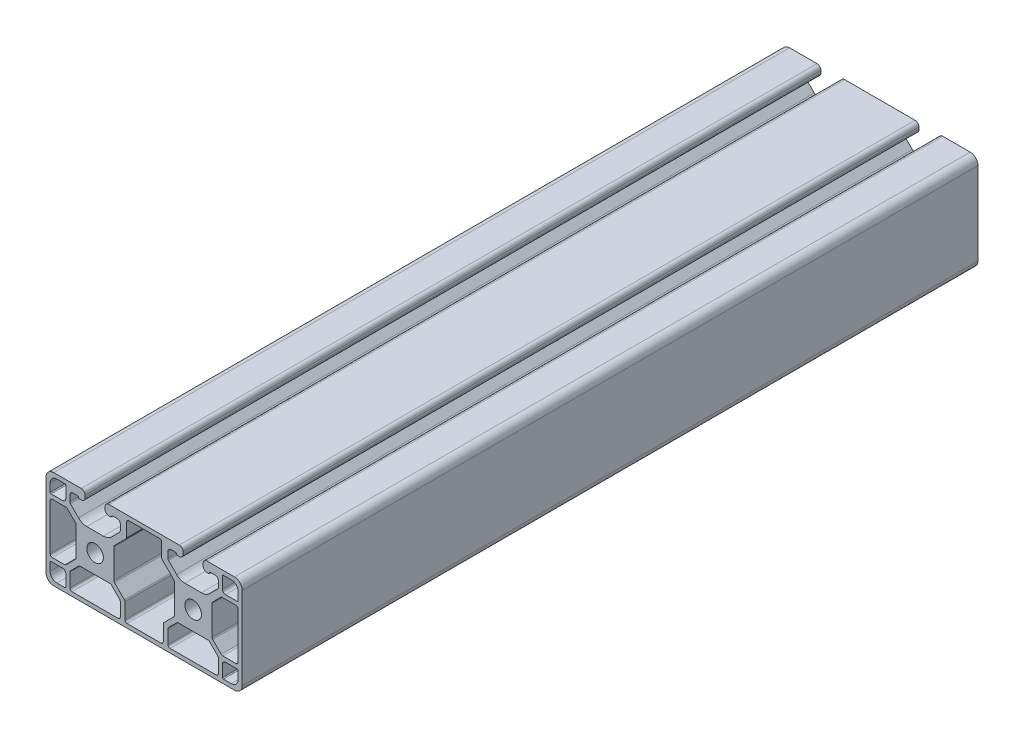
SolidWorks part; units mm, degrees
material "6105-T5 Aluminum"
ref_plane "Front Plane" through (0, 0, 0) normal (0, 0, 1) x (1, 0, 0)
ref_plane "Top Plane" through (0, 0, 0) normal (0, 1, 0) x (1, 0, 0)
ref_plane "Right Plane" through (0, 0, 0) normal (1, 0, 0) x (0, 0, -1)
sketch "Sketch1" plane through (0, 0, 0) normal (0, 0, 1) x (1, 0, 0)
  line L0 (18.3492, 15.5556) -> (18.3145, 12.3124)
  line L1 (17.9346, 11.9365) -> (13.2063, 11.9365)
  line L2 (11.9365, 13.2063) -> (11.9365, 17.9346)
  line L3 (12.3124, 18.3145) -> (15.5556, 18.3492)
  line L4 (15.5556, -18.3492) -> (12.3165, -18.3492)
  line L5 (11.9365, -17.9693) -> (11.9365, -13.2063)
  line L6 (13.2063, -11.9365) -> (17.9346, -11.9365)
  line L7 (18.3145, -12.3124) -> (18.3492, -15.5556)
  line L8 (-12.565, 11.308) -> (-7.9429, 6.6858)
  line L9 (-7.6825, 6.0573) -> (-7.6825, -5.8777)
  line L10 (-7.9429, -6.5062) -> (-11.9301, -10.4935)
  line L11 (-12.1905, -11.122) -> (-12.1905, -17.4603)
  line L12 (-13.0794, -18.3492) -> (-26.9206, -18.3492)
  line L13 (-27.8095, -17.4603) -> (-27.8095, -11.122)
  line L14 (-28.0699, -10.4935) -> (-32.0571, -6.5062)
  line L15 (-32.3175, -5.8777) -> (-32.3175, 6.0573)
  line L16 (-32.0571, 6.6858) -> (-27.435, 11.308)
  line L17 (-27.1746, 11.9365) -> (-27.1746, 17.4216)
  line L18 (-26.2857, 18.3105) -> (-13.7143, 18.3105)
  line L19 (-12.8254, 17.4216) -> (-12.8254, 11.9365)
  line L20 (-51.2824, 10.0254) -> (-47.9429, 6.6858)
  line L21 (-47.6825, 6.0573) -> (-47.6825, -5.5185)
  line L22 (-47.9429, -6.1471) -> (-51.8212, -10.0254)
  line L23 (-52.4497, -10.2857) -> (-57.4216, -10.2857)
  line L24 (-58.3105, -9.3968) -> (-58.3105, 9.3968)
  line L25 (-57.4216, 10.2857) -> (-51.911, 10.2857)
  line L26 (-58.3145, 12.3124) -> (-58.3492, 15.5556)
  line L27 (-55.5556, 18.3492) -> (-52.3124, 18.3145)
  line L28 (-51.9365, 17.9346) -> (-51.9365, 13.2063)
  line L29 (-53.2063, 11.9365) -> (-57.9346, 11.9365)
  line L30 (-52.3165, -18.3492) -> (-55.5556, -18.3492)
  line L31 (-58.3492, -15.5556) -> (-58.3145, -12.3124)
  line L32 (-57.9346, -11.9365) -> (-53.2063, -11.9365)
  line L33 (-51.9365, -13.2063) -> (-51.9365, -17.9693)
  line L34 (-46.0573, -7.6825) -> (-33.9427, -7.6825)
  line L35 (-33.3142, -7.9429) -> (-29.9746, -11.2824)
  line L36 (-29.7143, -11.911) -> (-29.7143, -17.4603)
  line L37 (-30.6032, -18.3492) -> (-49.3968, -18.3492)
  line L38 (-50.2857, -17.4603) -> (-50.2857, -11.911)
  line L39 (-50.0254, -11.2824) -> (-46.6858, -7.9429)
  line L40 (10.2857, -11.911) -> (10.2857, -17.4603)
  line L41 (9.3968, -18.3492) -> (-9.3968, -18.3492)
  line L42 (-10.2857, -17.4603) -> (-10.2857, -11.911)
  line L43 (-10.0254, -11.2824) -> (-6.6858, -7.9429)
  line L44 (-6.0573, -7.6825) -> (6.0572, -7.6825)
  line L45 (6.6858, -7.9429) -> (10.0253, -11.2824)
  line L46 (11.462, -10.0253) -> (7.9429, -6.5063)
  line L47 (7.6825, -5.8776) -> (7.6825, 6.0573)
  line L48 (7.9429, 6.6858) -> (11.2824, 10.0254)
  line L49 (11.911, 10.2857) -> (17.4216, 10.2857)
  line L50 (18.3105, 9.3968) -> (18.3105, -9.3968)
  line L51 (17.4216, -10.2857) -> (12.0906, -10.2857)
  line L52 (20, -16.8254) -> (20, 16.8254)
  line L53 (16.8254, 20) -> (5.6381, 20)
  line L54 (4.0635, 18.4254) -> (4.0635, 17.5111)
  line L55 (5.6381, 15.9365) -> (6.3446, 15.9365)
  line L56 (6.7243, 16.3032) -> (6.7253, 16.3317)
  line L57 (7.105, 16.6984) -> (9.0159, 16.6984)
  line L58 (10.2857, 15.4286) -> (10.2857, 12.9885)
  line L59 (10.0254, 12.3599) -> (6.739, 9.0736)
  line L60 (3.3808, 7.6825) -> (-3.3808, 7.6825)
  line L61 (-6.739, 9.0736) -> (-10.0254, 12.3599)
  line L62 (-10.2857, 12.9885) -> (-10.2857, 15.4286)
  line L63 (-9.0159, 16.6984) -> (-7.105, 16.6984)
  line L64 (-6.7253, 16.3317) -> (-6.7243, 16.3032)
  line L65 (-6.3446, 15.9365) -> (-5.6381, 15.9365)
  line L66 (-4.0635, 17.5111) -> (-4.0635, 18.4254)
  line L67 (-5.6381, 20) -> (-34.3619, 20)
  line L68 (-35.9365, 18.4254) -> (-35.9365, 17.5111)
  line L69 (-34.3619, 15.9365) -> (-33.6554, 15.9365)
  line L70 (-33.2757, 16.3032) -> (-33.2747, 16.3317)
  line L71 (-32.895, 16.6984) -> (-30.9841, 16.6984)
  line L72 (-29.7143, 15.4286) -> (-29.7143, 12.9885)
  line L73 (-29.9746, 12.3599) -> (-33.261, 9.0736)
  line L74 (-36.6192, 7.6825) -> (-43.3808, 7.6825)
  line L75 (-46.739, 9.0736) -> (-50.0254, 12.3599)
  line L76 (-50.2857, 12.9885) -> (-50.2857, 15.4286)
  line L77 (-49.0159, 16.6984) -> (-47.105, 16.6984)
  line L78 (-46.7253, 16.3317) -> (-46.7243, 16.3032)
  line L79 (-46.3446, 15.9365) -> (-45.6381, 15.9365)
  line L80 (-44.0635, 17.5111) -> (-44.0635, 18.4254)
  line L81 (-45.6381, 20) -> (-56.8254, 20)
  line L82 (-60, 16.8254) -> (-60, -16.8254)
  line L83 (-56.8254, -20) -> (16.8254, -20)
  arc A0 (17.9346, 11.9365) -> (18.3145, 12.3124) centre (17.9346, 12.3165) ccw
  arc A1 (11.9365, 13.2063) -> (13.2063, 11.9365) centre (13.2063, 13.2063) ccw
  arc A2 (12.3124, 18.3145) -> (11.9365, 17.9346) centre (12.3165, 17.9346) ccw
  arc A3 (18.3492, 15.5556) -> (15.5556, 18.3492) centre (15.5556, 15.5556) ccw
  arc A4 (11.9365, -17.9693) -> (12.3165, -18.3492) centre (12.3165, -17.9693) ccw
  arc A5 (13.2063, -11.9365) -> (11.9365, -13.2063) centre (13.2063, -13.2063) ccw
  arc A6 (18.3145, -12.3124) -> (17.9346, -11.9365) centre (17.9346, -12.3165) ccw
  arc A7 (15.5556, -18.3492) -> (18.3492, -15.5556) centre (15.5556, -15.5556) ccw
  arc A8 (-12.8254, 11.9365) -> (-12.565, 11.308) centre (-11.9365, 11.9365) ccw
  arc A9 (-7.6825, 6.0573) -> (-7.9429, 6.6858) centre (-8.5714, 6.0573) ccw
  arc A10 (-7.9429, -6.5062) -> (-7.6825, -5.8777) centre (-8.5714, -5.8777) ccw
  arc A11 (-11.9301, -10.4935) -> (-12.1905, -11.122) centre (-11.3016, -11.122) ccw
  arc A12 (-13.0794, -18.3492) -> (-12.1905, -17.4603) centre (-13.0794, -17.4603) ccw
  arc A13 (-27.8095, -17.4603) -> (-26.9206, -18.3492) centre (-26.9206, -17.4603) ccw
  arc A14 (-27.8095, -11.122) -> (-28.0699, -10.4935) centre (-28.6984, -11.122) ccw
  arc A15 (-32.3175, -5.8777) -> (-32.0571, -6.5062) centre (-31.4286, -5.8777) ccw
  arc A16 (-32.0571, 6.6858) -> (-32.3175, 6.0573) centre (-31.4286, 6.0573) ccw
  arc A17 (-27.435, 11.308) -> (-27.1746, 11.9365) centre (-28.0635, 11.9365) ccw
  arc A18 (-26.2857, 18.3105) -> (-27.1746, 17.4216) centre (-26.2857, 17.4216) ccw
  arc A19 (-12.8254, 17.4216) -> (-13.7143, 18.3105) centre (-13.7143, 17.4216) ccw
  arc A20 (-51.2824, 10.0254) -> (-51.911, 10.2857) centre (-51.911, 9.3968) ccw
  arc A21 (-47.6825, 6.0573) -> (-47.9429, 6.6858) centre (-48.5714, 6.0573) ccw
  arc A22 (-47.9429, -6.1471) -> (-47.6825, -5.5185) centre (-48.5714, -5.5185) ccw
  arc A23 (-52.4497, -10.2857) -> (-51.8212, -10.0254) centre (-52.4497, -9.3968) ccw
  arc A24 (-58.3105, -9.3968) -> (-57.4216, -10.2857) centre (-57.4216, -9.3968) ccw
  arc A25 (-57.4216, 10.2857) -> (-58.3105, 9.3968) centre (-57.4216, 9.3968) ccw
  arc A26 (-58.3145, 12.3124) -> (-57.9346, 11.9365) centre (-57.9346, 12.3165) ccw
  arc A27 (-55.5556, 18.3492) -> (-58.3492, 15.5556) centre (-55.5556, 15.5556) ccw
  arc A28 (-51.9365, 17.9346) -> (-52.3124, 18.3145) centre (-52.3165, 17.9346) ccw
  arc A29 (-53.2063, 11.9365) -> (-51.9365, 13.2063) centre (-53.2063, 13.2063) ccw
  arc A30 (-52.3165, -18.3492) -> (-51.9365, -17.9693) centre (-52.3165, -17.9693) ccw
  arc A31 (-58.3492, -15.5556) -> (-55.5556, -18.3492) centre (-55.5556, -15.5556) ccw
  arc A32 (-57.9346, -11.9365) -> (-58.3145, -12.3124) centre (-57.9346, -12.3165) ccw
  arc A33 (-51.9365, -13.2063) -> (-53.2063, -11.9365) centre (-53.2063, -13.2063) ccw
  arc A34 (-46.0573, -7.6825) -> (-46.6858, -7.9429) centre (-46.0573, -8.5714) ccw
  arc A35 (-33.3142, -7.9429) -> (-33.9427, -7.6825) centre (-33.9427, -8.5714) ccw
  arc A36 (-29.7143, -11.911) -> (-29.9746, -11.2824) centre (-30.6032, -11.911) ccw
  arc A37 (-30.6032, -18.3492) -> (-29.7143, -17.4603) centre (-30.6032, -17.4603) ccw
  arc A38 (-50.2857, -17.4603) -> (-49.3968, -18.3492) centre (-49.3968, -17.4603) ccw
  arc A39 (-50.0254, -11.2824) -> (-50.2857, -11.911) centre (-49.3968, -11.911) ccw
  arc A40 (10.2857, -11.911) -> (10.0253, -11.2824) centre (9.3967, -11.911) ccw
  arc A41 (9.3968, -18.3492) -> (10.2857, -17.4603) centre (9.3968, -17.4603) ccw
  arc A42 (-10.2857, -17.4603) -> (-9.3968, -18.3492) centre (-9.3968, -17.4603) ccw
  arc A43 (-10.0254, -11.2824) -> (-10.2857, -11.911) centre (-9.3968, -11.911) ccw
  arc A44 (-6.0573, -7.6825) -> (-6.6858, -7.9429) centre (-6.0573, -8.5714) ccw
  arc A45 (6.6858, -7.9429) -> (6.0572, -7.6825) centre (6.0572, -8.5715) ccw
  arc A46 (7.6825, -5.8776) -> (7.9429, -6.5063) centre (8.5715, -5.8776) ccw
  arc A47 (7.9429, 6.6858) -> (7.6825, 6.0573) centre (8.5714, 6.0573) ccw
  arc A48 (11.911, 10.2857) -> (11.2824, 10.0254) centre (11.911, 9.3968) ccw
  arc A49 (18.3105, 9.3968) -> (17.4216, 10.2857) centre (17.4216, 9.3968) ccw
  arc A50 (17.4216, -10.2857) -> (18.3105, -9.3968) centre (17.4216, -9.3968) ccw
  arc A51 (11.462, -10.0253) -> (12.0906, -10.2857) centre (12.0906, -9.3967) ccw
  circle A52 centre (0, 0) radius 3.3778
  circle A53 centre (-40, 0) radius 3.3778
  arc A54 (16.8254, -20) -> (20, -16.8254) centre (16.8254, -16.8254) ccw
  arc A55 (20, 16.8254) -> (16.8254, 20) centre (16.8254, 16.8254) ccw
  arc A56 (5.6381, 20) -> (4.0635, 18.4254) centre (5.6381, 18.4254) ccw
  arc A57 (4.0635, 17.5111) -> (5.6381, 15.9365) centre (5.6381, 17.5111) ccw
  arc A58 (6.3446, 15.9365) -> (6.7243, 16.3032) centre (6.3446, 16.3165) ccw
  arc A59 (7.105, 16.6984) -> (6.7253, 16.3317) centre (7.105, 16.3185) ccw
  arc A60 (10.2857, 15.4286) -> (9.0159, 16.6984) centre (9.0159, 15.4286) ccw
  arc A61 (10.0254, 12.3599) -> (10.2857, 12.9885) centre (9.3968, 12.9885) ccw
  arc A62 (3.3808, 7.6825) -> (6.739, 9.0736) centre (3.3808, 12.4317) ccw
  arc A63 (-6.739, 9.0736) -> (-3.3808, 7.6825) centre (-3.3808, 12.4317) ccw
  arc A64 (-10.2857, 12.9885) -> (-10.0254, 12.3599) centre (-9.3968, 12.9885) ccw
  arc A65 (-9.0159, 16.6984) -> (-10.2857, 15.4286) centre (-9.0159, 15.4286) ccw
  arc A66 (-6.7253, 16.3317) -> (-7.105, 16.6984) centre (-7.105, 16.3185) ccw
  arc A67 (-6.7243, 16.3032) -> (-6.3446, 15.9365) centre (-6.3446, 16.3165) ccw
  arc A68 (-5.6381, 15.9365) -> (-4.0635, 17.5111) centre (-5.6381, 17.5111) ccw
  arc A69 (-4.0635, 18.4254) -> (-5.6381, 20) centre (-5.6381, 18.4254) ccw
  arc A70 (-34.3619, 20) -> (-35.9365, 18.4254) centre (-34.3619, 18.4254) ccw
  arc A71 (-35.9365, 17.5111) -> (-34.3619, 15.9365) centre (-34.3619, 17.5111) ccw
  arc A72 (-33.6554, 15.9365) -> (-33.2757, 16.3032) centre (-33.6554, 16.3165) ccw
  arc A73 (-32.895, 16.6984) -> (-33.2747, 16.3317) centre (-32.895, 16.3185) ccw
  arc A74 (-29.7143, 15.4286) -> (-30.9841, 16.6984) centre (-30.9841, 15.4286) ccw
  arc A75 (-29.9746, 12.3599) -> (-29.7143, 12.9885) centre (-30.6032, 12.9885) ccw
  arc A76 (-36.6192, 7.6825) -> (-33.261, 9.0736) centre (-36.6192, 12.4317) ccw
  arc A77 (-46.739, 9.0736) -> (-43.3808, 7.6825) centre (-43.3808, 12.4317) ccw
  arc A78 (-50.2857, 12.9885) -> (-50.0254, 12.3599) centre (-49.3968, 12.9885) ccw
  arc A79 (-49.0159, 16.6984) -> (-50.2857, 15.4286) centre (-49.0159, 15.4286) ccw
  arc A80 (-46.7253, 16.3317) -> (-47.105, 16.6984) centre (-47.105, 16.3185) ccw
  arc A81 (-46.7243, 16.3032) -> (-46.3446, 15.9365) centre (-46.3446, 16.3165) ccw
  arc A82 (-45.6381, 15.9365) -> (-44.0635, 17.5111) centre (-45.6381, 17.5111) ccw
  arc A83 (-44.0635, 18.4254) -> (-45.6381, 20) centre (-45.6381, 18.4254) ccw
  arc A84 (-56.8254, 20) -> (-60, 16.8254) centre (-56.8254, 16.8254) ccw
  arc A85 (-60, -16.8254) -> (-56.8254, -20) centre (-56.8254, -16.8254) ccw
extrude "Extrude1" add sketch "Sketch1" against normal blind 300
